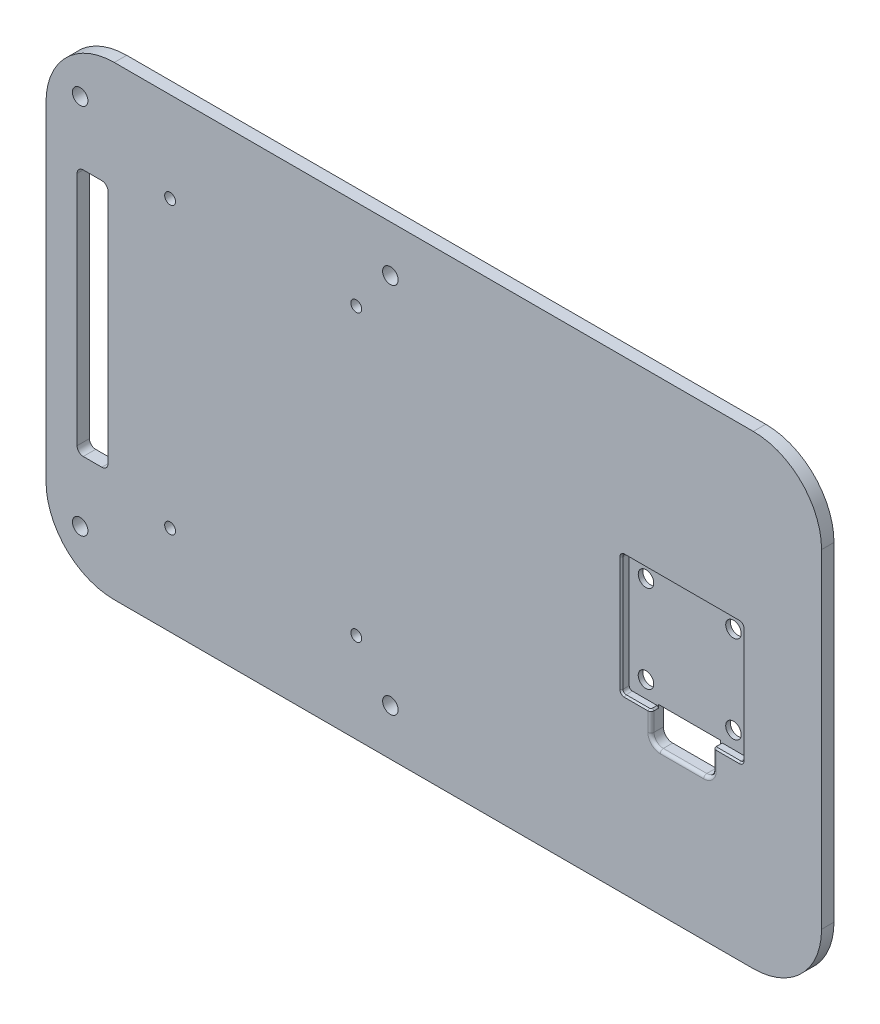
SolidWorks part; units mm, degrees
ref_plane "前视基准面" through (0, 0, 0) normal (0, 0, 1) x (1, 0, 0)
ref_plane "上视基准面" through (0, 0, 0) normal (0, 1, 0) x (1, 0, 0)
ref_plane "右视基准面" through (0, 0, 0) normal (1, 0, 0) x (0, 0, -1)
other "Configuration Table"
sketch "草图1" plane through (0, 0, 0) normal (0, 0, 1) x (1, 0, 0)
  line L0 (-1113.7626, 0) -> (48886.2374, 0) construction
  line L1 (-103, -75) -> (103, -75)
  line L2 (-125, -53) -> (-125, 53)
  line L3 (-103, 75) -> (103, 75)
  line L4 (125, -53) -> (125, 53)
  line L5 (-125, -75) -> (125, 75) construction
  line L6 (-125, 75) -> (125, -75) construction
  line L7 (-64, -1009.8705) -> (-64, 48990.1295) construction
  line L8 (-55, -1000) -> (-55, 49000) construction
  line L9 (-113, -40) -> (-107, -40)
  line L10 (-115, -38) -> (-115, 38)
  line L11 (-113, 40) -> (-107, 40)
  line L12 (-105, -38) -> (-105, 38)
  line L13 (-115, -40) -> (-105, 40) construction
  line L14 (-115, 40) -> (-105, -40) construction
  line L16 (-89, -50) -> (-21, -50) construction
  line L17 (-89, -50) -> (-89, 50) construction
  line L18 (-89, 50) -> (-21, 50) construction
  line L19 (-21, -50) -> (-21, 50) construction
  line L20 (-89, -50) -> (-21, 50) construction
  line L21 (-89, 50) -> (-21, -50) construction
  line L22 (70, -29) -> (90, -29)
  line L23 (70, -29) -> (70, -19)
  line L24 (70, -19) -> (90, -19)
  line L25 (90, -29) -> (90, -19)
  line L26 (70, -29) -> (90, -19) construction
  line L27 (70, -19) -> (90, -29) construction
  arc A0 (103, 75) -> (125, 53) centre (103, 53) cw
  arc A1 (103, -75) -> (125, -53) centre (103, -53) ccw
  arc A2 (-103, -75) -> (-125, -53) centre (-103, -53) cw
  arc A3 (-125, 53) -> (-103, 75) centre (-103, 53) cw
  circle A4 centre (-114, 60) radius 2.5
  circle A5 centre (-114, -60) radius 2.5
  circle A6 centre (-14, -60) radius 2.5
  circle A7 centre (-14, 60) radius 2.5
  arc A8 (-107, -40) -> (-105, -38) centre (-107, -38) ccw
  arc A9 (-113, -40) -> (-115, -38) centre (-113, -38) cw
  arc A10 (-105, 38) -> (-107, 40) centre (-107, 38) ccw
  arc A11 (-115, 38) -> (-113, 40) centre (-113, 38) cw
  circle A12 centre (-85, 46) radius 1.75
  circle A13 centre (-25, 46) radius 1.75
  circle A14 centre (-25, -46) radius 1.75
  circle A15 centre (-85, -46) radius 1.75
  point P0 (0, 0)
  point P30 (-110, 0)
  point P57 (-55, 0)
  point P62 (80, -29)
  point P63 (80, -24)
  point P68 (0, 0)
  point P69 (59.5565, -21.0445)
  point P70 (0, 0)
  dimension "D3" = 22
  dimension "D4" = 5
  dimension "D6" = 11
  dimension "D7" = 15
  dimension "D8" = 120
  dimension "D12" = 2
  dimension "D13" = 3.5
  dimension "D14" = 92
  dimension "D15" = 60
  dimension "D1" = 150
  dimension "D2" = 250
  dimension "D5" = 50
  dimension "D9" = 10
  dimension "D10" = 10
  dimension "D11" = 80
  dimension "D16" = 70
  dimension "D17" = 68
  dimension "D18" = 100
  dimension "D19" = 20
  dimension "D20" = 10
  dimension "D21" = 24
  dimension "D22" = 70
extrude "凸台-拉伸1" add sketch "草图1" along normal blind 4
sketch "草图2" plane through (0, 0, 4) normal (0, 0, 1) x (1, 0, 0)
  line L0 (-1000, 0) -> (49000, 0) construction
  line L1 (60.5, -19.5) -> (99.5, -19.5)
  line L2 (60.5, -19.5) -> (60.5, 19.5)
  line L3 (60.5, 19.5) -> (99.5, 19.5)
  line L4 (99.5, -19.5) -> (99.5, 19.5)
  line L5 (60.5, -19.5) -> (99.5, 19.5) construction
  line L6 (60.5, 19.5) -> (99.5, -19.5) construction
  line L7 (0, -1000) -> (0, 49000) construction
  point P0 (80, 0)
  point P9 (0, 0)
  dimension "D1" = 39
  dimension "D2" = 39
  dimension "D3" = 80
extrude "切除-拉伸1" cut sketch "草图2" against normal blind 2.5
fillet "圆角1" radius 3 2 edges at (70, -29, 2) (90, -29, 2)
fillet "圆角2" radius 1 9 edges at (80, -29, 4) (70.8787, -28.1213, 4) (70, -22.75, 4) (60.5, -19.5, 2.75) (99.5, -19.5, 2.75) (99.5, 19.5, 2.75) (60.5, 19.5, 2.75) (89.1213, -28.1213, 4) (90, -22.75, 4)
chamfer "倒角1" distance 0.5 angle 45 13 edges at (60.7929, -19.2071, 4) (65.25, -19.5, 4) (94.75, -19.5, 4) (99.2071, -19.2071, 4) (99.5, 0, 4) (99.2071, 19.2071, 4) (80, 19.5, 4) (60.7929, 19.2071, 4) (60.5, 0, 4) (90, -19.5, 2.25) (90.2929, -19.5, 3.7071) (70, -19.5, 2.25) (69.7071, -19.5, 3.7071)
sketch "草图4" plane through (0, 0, 1.5) normal (0, 0, 1) x (1, 0, 0)
  line L0 (61.5, -18.5) -> (98.5, 18.5) construction
  line L1 (61.5, 18.5) -> (98.5, -18.5) construction
  line L2 (-920, 0) -> (49080, 0) construction
  line L3 (80, -1000) -> (80, 49000) construction
  line L10 (60.5, 18.5) -> (60.5, -18.5)
  line L11 (61.5, -19.5) -> (69.5, -19.5)
  line L12 (69.5, -19.5) -> (70, -20)
  line L13 (70, -20) -> (70, -19)
  line L14 (70, -19) -> (90, -19)
  line L15 (90, -19) -> (90, -20)
  line L16 (90, -20) -> (90.5, -19.5)
  line L17 (90.5, -19.5) -> (98.5, -19.5)
  line L18 (99.5, -18.5) -> (99.5, 18.5)
  line L19 (98.5, 19.5) -> (61.5, 19.5)
  line L20 (60.5, 18.5) -> (60.5, -18.5) construction
  line L21 (61.5, -19.5) -> (69.5, -19.5) construction
  line L22 (69.5, -19.5) -> (70, -20) construction
  line L23 (70, -20) -> (70, -19) construction
  line L24 (70, -19) -> (90, -19) construction
  line L25 (90, -19) -> (90, -20) construction
  line L26 (90, -20) -> (90.5, -19.5) construction
  line L27 (90.5, -19.5) -> (98.5, -19.5) construction
  line L28 (99.5, -18.5) -> (99.5, 18.5) construction
  line L29 (98.5, 19.5) -> (61.5, 19.5) construction
  circle A0 centre (65.9003, -14.0997) radius 2.5
  circle A2 centre (94.0997, -14.0997) radius 2.5
  circle A3 centre (94.0997, 14.0997) radius 2.5
  arc A4 (60.5, -18.5) -> (61.5, -19.5) centre (61.5, -18.5) ccw
  arc A5 (98.5, -19.5) -> (99.5, -18.5) centre (98.5, -18.5) ccw
  arc A6 (99.5, 18.5) -> (98.5, 19.5) centre (98.5, 18.5) ccw
  arc A7 (61.5, 19.5) -> (60.5, 18.5) centre (61.5, 18.5) ccw
  arc A8 (60.5, -18.5) -> (61.5, -19.5) centre (61.5, -18.5) ccw construction
  arc A9 (98.5, -19.5) -> (99.5, -18.5) centre (98.5, -18.5) ccw construction
  arc A10 (99.5, 18.5) -> (98.5, 19.5) centre (98.5, 18.5) ccw construction
  arc A11 (61.5, 19.5) -> (60.5, 18.5) centre (61.5, 18.5) ccw construction
  circle A12 centre (65.9003, 14.0997) radius 2.5
  point P19 (80, 0)
  dimension "D2" = 5
  dimension "D3" = 39.88
  dimension "D1" = 0
extrude "切除-拉伸2" cut sketch "草图4" against normal blind 2
